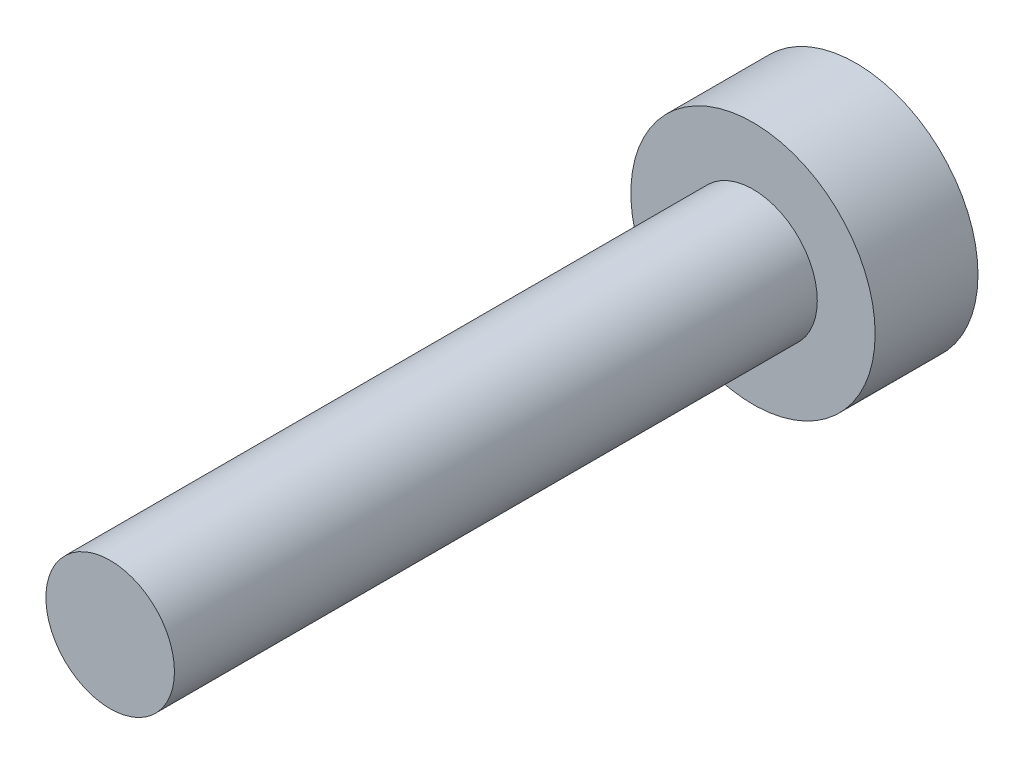
SolidWorks part; units mm, degrees
ref_plane "前视基准面" through (0, 0, 0) normal (0, 0, 1) x (1, 0, 0)
ref_plane "上视基准面" through (0, 0, 0) normal (0, 1, 0) x (1, 0, 0)
ref_plane "右视基准面" through (0, 0, 0) normal (1, 0, 0) x (0, 0, -1)
sketch "草图1" plane through (0, 0, 0) normal (0, 0, 1) x (1, 0, 0)
  circle A0 centre (0, 0) radius 1
  dimension "D1" = 2
extrude "公称杆长10_无牙型参考" add sketch "草图1" along normal blind 10
sketch "草图2" plane through (0, 0, 0) normal (0, 0, 1) x (1, 0, 0)
  circle A0 centre (0, 0) radius 1.9
  dimension "D1" = 3.8
extrude "螺丝头_端面为长度基准" add sketch "草图2" along normal blind 1.6 from offset 1.6
